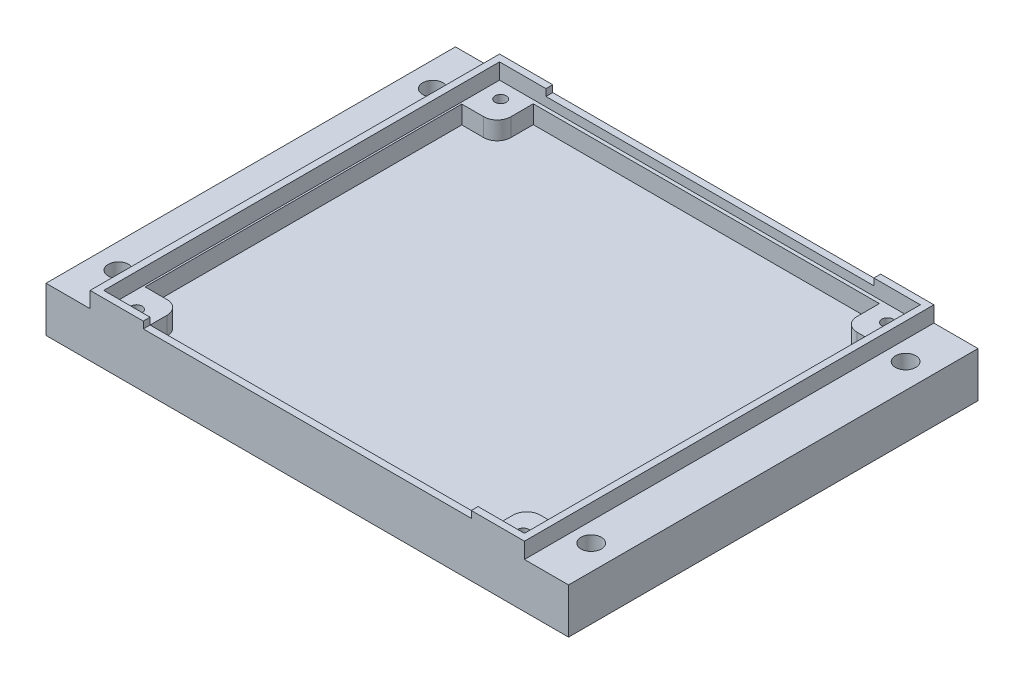
SolidWorks part; units mm, degrees
ref_plane "Front Plane" through (0, 0, 0) normal (0, 0, 1) x (1, 0, 0)
ref_plane "Top Plane" through (0, 0, 0) normal (0, 1, 0) x (1, 0, 0)
ref_plane "Right Plane" through (0, 0, 0) normal (1, 0, 0) x (0, 0, -1)
sketch "Sketch1" plane through (0, 0, 0) normal (0, 1, 0) x (1, 0, 0)
  line L1 (-57.75, 45.25) -> (57.75, 45.25)
  line L2 (-57.75, 45.25) -> (-57.75, -45.25)
  line L3 (-57.75, -45.25) -> (57.75, -45.25)
  line L4 (57.75, 45.25) -> (57.75, -45.25)
  line L5 (-57.75, 45.25) -> (57.75, -45.25) construction
  line L6 (-57.75, -45.25) -> (57.75, 45.25) construction
  point P0 (0, 0)
  dimension "D1" = 115.5
  dimension "D2" = 90.5
extrude "Boss-Extrude1" add sketch "Sketch1" along normal blind 10
sketch "Sketch2" plane through (0, 10, 0) normal (0, 1, 0) x (1, 0, 0)
  line L0 (0, 45.25) -> (0, -45.25) construction
  line L1 (57.75, 45.25) -> (-57.75, 45.25) construction
  line L2 (-57.75, -45.25) -> (57.75, -45.25) construction
  line L3 (-57.75, 0) -> (57.75, 0) construction
  line L4 (-57.75, 45.25) -> (-57.75, -45.25) construction
  line L5 (57.75, -45.25) -> (57.75, 45.25) construction
  line L6 (-46.5, 43.75) -> (-46.5, -43.75)
  line L7 (-48, 45.25) -> (48, 45.25)
  line L8 (-48, 45.25) -> (-48, -45.25)
  line L9 (-48, -45.25) -> (48, -45.25)
  line L10 (48, 45.25) -> (48, -45.25)
  line L11 (-48, 45.25) -> (48, -45.25) construction
  line L12 (-48, -45.25) -> (48, 45.25) construction
  line L13 (-46.5, -43.75) -> (46.5, -43.75)
  line L14 (46.5, 43.75) -> (46.5, -43.75)
  line L15 (-46.5, 43.75) -> (46.5, 43.75)
  point P12 (0, 0)
  dimension "D1" = 96
  dimension "D2" = 1.5
extrude "Boss-Extrude2" add sketch "Sketch2" along normal blind 3.5
sketch "Sketch3" plane through (0, 10, 0) normal (0, 1, 0) x (1, 0, 0)
  line L0 (0, 43.75) -> (0, -43.75) construction
  line L1 (46.5, 43.75) -> (-46.5, 43.75) construction
  line L2 (-46.5, -43.75) -> (46.5, -43.75) construction
  line L3 (46.5, 0) -> (-46.5, 0) construction
  line L5 (-46.5, 43.75) -> (-46.5, -43.75) construction
  line L6 (46.5, -43.75) -> (46.5, 43.75) construction
  circle A0 centre (-42.75, 40.25) radius 1.25
  circle A1 centre (42.75, 40.25) radius 1.25
  circle A2 centre (42.75, -40.25) radius 1.25
  circle A3 centre (-42.75, -40.25) radius 1.25
  dimension "D1" = 42.75
  dimension "D3" = 2.5
  dimension "D2" = 40.25
extrude "Cut-Extrude1" cut sketch "Sketch3" against normal blind 20
sketch "Sketch4" plane through (0, 10, 0) normal (0, 1, 0) x (1, 0, 0)
  line L0 (0, 43.75) -> (0, -43.75) construction
  line L1 (46.5, 43.75) -> (-46.5, 43.75) construction
  line L2 (-46.5, -43.75) -> (46.5, -43.75) construction
  line L3 (-46.5, 0) -> (46.5, 0) construction
  line L4 (-46.5, 43.75) -> (-46.5, -43.75) construction
  line L5 (46.5, -43.75) -> (46.5, 43.75) construction
  line L6 (-38.25, 42.95) -> (38.25, 42.95)
  line L7 (-38.25, 35) -> (-46.1, 35)
  line L8 (-38.25, 35) -> (-38.25, 42.95)
  line L9 (46.1, 35) -> (46.1, -35)
  line L10 (38.25, 35) -> (38.25, 42.95)
  line L11 (48, 45.25) -> (-48, 45.25) construction
  line L12 (-46.1, 35) -> (-46.1, -35)
  line L13 (-48, 45.25) -> (-48, -45.25) construction
  line L14 (38.25, 35) -> (46.1, 35)
  line L15 (38.25, -35) -> (46.1, -35)
  line L16 (38.25, -35) -> (38.25, -42.95)
  line L17 (-38.25, -35) -> (-38.25, -42.95)
  line L18 (-38.25, -35) -> (-46.1, -35)
  line L19 (-38.25, -42.95) -> (38.25, -42.95)
  point P26 (0, 42.95)
  point P27 (46.1, 0)
  point P28 (-46.1, 0)
  point P32 (0, -42.95)
  dimension "D1" = 38.25
  dimension "D2" = 35
  dimension "D3" = 2.3
  dimension "D4" = 1.9
extrude "Cut-Extrude2" cut sketch "Sketch4" against normal blind 4
fillet "Fillet1" radius 3 4 edges at (38.25, 8, 35) (38.25, 8, -35) (-38.25, 8, 35) (-38.25, 8, -35)
sketch "Sketch5" plane through (0, 10, 0) normal (0, 1, 0) x (1, 0, 0)
  line L0 (0, 45.25) -> (0, -45.25) construction
  line L1 (48, 45.25) -> (-48, 45.25) construction
  line L2 (-48, -45.25) -> (48, -45.25) construction
  line L3 (-57.75, 0) -> (57.75, 0) construction
  line L4 (-57.75, 45.25) -> (-57.75, -45.25) construction
  line L5 (57.75, -45.25) -> (57.75, 45.25) construction
  circle A0 centre (-52.25, 34.75) radius 2.25
  circle A1 centre (52.25, 34.75) radius 2.25
  circle A2 centre (52.25, -34.75) radius 2.25
  circle A3 centre (-52.25, -34.75) radius 2.25
  dimension "D1" = 52.25
  dimension "D2" = 34.75
  dimension "D3" = 4.5
extrude "Cut-Extrude3" cut sketch "Sketch5" against normal blind 15
sketch "Sketch6" plane through (0, 0, 45.25) normal (0, 0, 1) x (1, 0, 0)
  line L0 (0, 13.5) -> (0, 0) construction
  line L1 (-48, 13.5) -> (48, 13.5) construction
  line L2 (-57.75, 0) -> (57.75, 0) construction
  line L4 (-36.25, 22.5019) -> (36.25, 22.5019)
  line L5 (-36.25, 22.5019) -> (-36.25, 12)
  line L6 (-36.25, 12) -> (36.25, 12)
  line L7 (36.25, 22.5019) -> (36.25, 12)
  dimension "D1" = 72.5
  dimension "D2" = 36.25
  dimension "D3" = 1.5
extrude "Cut-Extrude4" cut sketch "Sketch6" against normal blind 98
sketch "Sketch7" plane through (0, 10, 0) normal (0, 1, 0) x (1, 0, 0)
  line L0 (-36.25, 43.75) -> (-36.25, -43.75) construction
  line L1 (36.25, 43.75) -> (36.25, -43.75) construction
  line L2 (-36.25, 34.75) -> (36.25, 34.75) construction
  line L3 (-36.25, 45.25) -> (36.25, 45.25) construction
  line L4 (-36.25, 32.75) -> (36.25, 32.75) construction
  line L5 (-57.75, 0) -> (57.75, 0) construction
  line L8 (-57.75, 45.25) -> (-57.75, -45.25) construction
  line L9 (57.75, -45.25) -> (57.75, 45.25) construction
  line L10 (-36.25, -32.75) -> (36.25, -32.75) construction
  line L11 (-36.25, -34.75) -> (36.25, -34.75) construction
  dimension "D1" = 10.5
  dimension "D2" = 2
